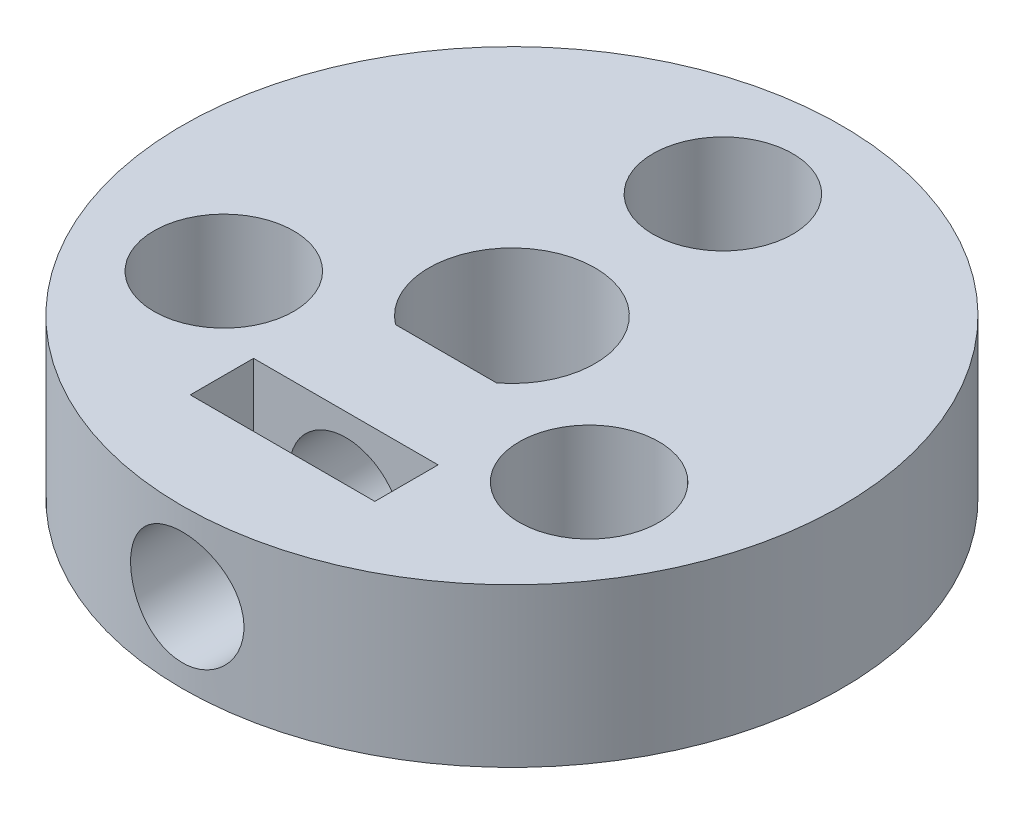
SolidWorks part; units mm, degrees
ref_plane "Front Plane" through (0, 0, 0) normal (0, 0, 1) x (1, 0, 0)
ref_plane "Top Plane" through (0, 0, 0) normal (0, 1, 0) x (1, 0, 0)
ref_plane "Right Plane" through (0, 0, 0) normal (1, 0, 0) x (0, 0, -1)
sketch "Sketch1" plane through (0, 0, 0) normal (0, 1, 0) x (1, 0, 0)
  circle A0 centre (0, 0) radius 12.5
  dimension "D1" = 25
extrude "Boss-Extrude1" add sketch "Sketch1" along normal blind 6
sketch "Sketch2" plane through (0, 6, 0) normal (0, 1, 0) x (1, 0, 0)
  line L0 (-1.9164, -2.5) -> (1.9164, -2.5)
  line L1 (0, -2.5) -> (0, 3.15) construction
  circle A0 centre (0, 0) radius 3.15
  dimension "D1" = 6.3
  dimension "D2" = 5.65
extrude "Cut-Extrude1" cut sketch "Sketch2" against normal up to next contours L0 L1 A0 | L1 L0 A0
sketch "Sketch3" plane through (0, 6, 0) normal (0, 1, 0) x (1, 0, 0)
  line L0 (0, -2.5) -> (0, -12.5) construction
  line L1 (-1.9164, -2.5) -> (1.9164, -2.5) construction
  line L3 (-3.5, -8.7) -> (3.5, -8.7)
  line L4 (-3.5, -8.7) -> (-3.5, -6.3)
  line L5 (-3.5, -6.3) -> (3.5, -6.3)
  line L6 (3.5, -8.7) -> (3.5, -6.3)
  line L7 (-3.5, -8.7) -> (3.5, -6.3) construction
  line L8 (-3.5, -6.3) -> (3.5, -8.7) construction
  circle A0 centre (0, 0) radius 12.5 construction
  point P7 (0, -7.5)
  dimension "D1" = 2.4
  dimension "D2" = 7
extrude "Cut-Extrude2" cut sketch "Sketch3" against normal up to next
sketch "Sketch4" plane through (0, 0, 2.5) normal (0, 0, -1) x (-1, 0, 0)
  line L0 (0, 0) -> (0, 6) construction
  line L1 (-1.9164, 0) -> (1.9164, 0) construction
  line L2 (1.9164, 6) -> (-1.9164, 6) construction
  circle A0 centre (0, 3) radius 2.15
  dimension "D1" = 4.3
extrude "Cut-Extrude3" cut sketch "Sketch4" against normal through all
sketch "Sketch5" plane through (0, 6, 0) normal (0, 1, 0) x (1, 0, 0)
  line L0 (0, 12.5) -> (0, 0) construction
  circle A2 centre (0, 8) radius 2.65
  circle A5 centre (0, 0) radius 12.5 construction
  circle A6 centre (6.9282, -4) radius 2.65
  circle A7 centre (-6.9282, -4) radius 2.65
  point P14 (0, 0)
  dimension "D1" = 5.3
  dimension "D3" = 4
  dimension "D4" = 6.9282
  dimension "D5" = 8
  dimension "D2" = 3
extrude "Cut-Extrude4" cut sketch "Sketch5" against normal through all
